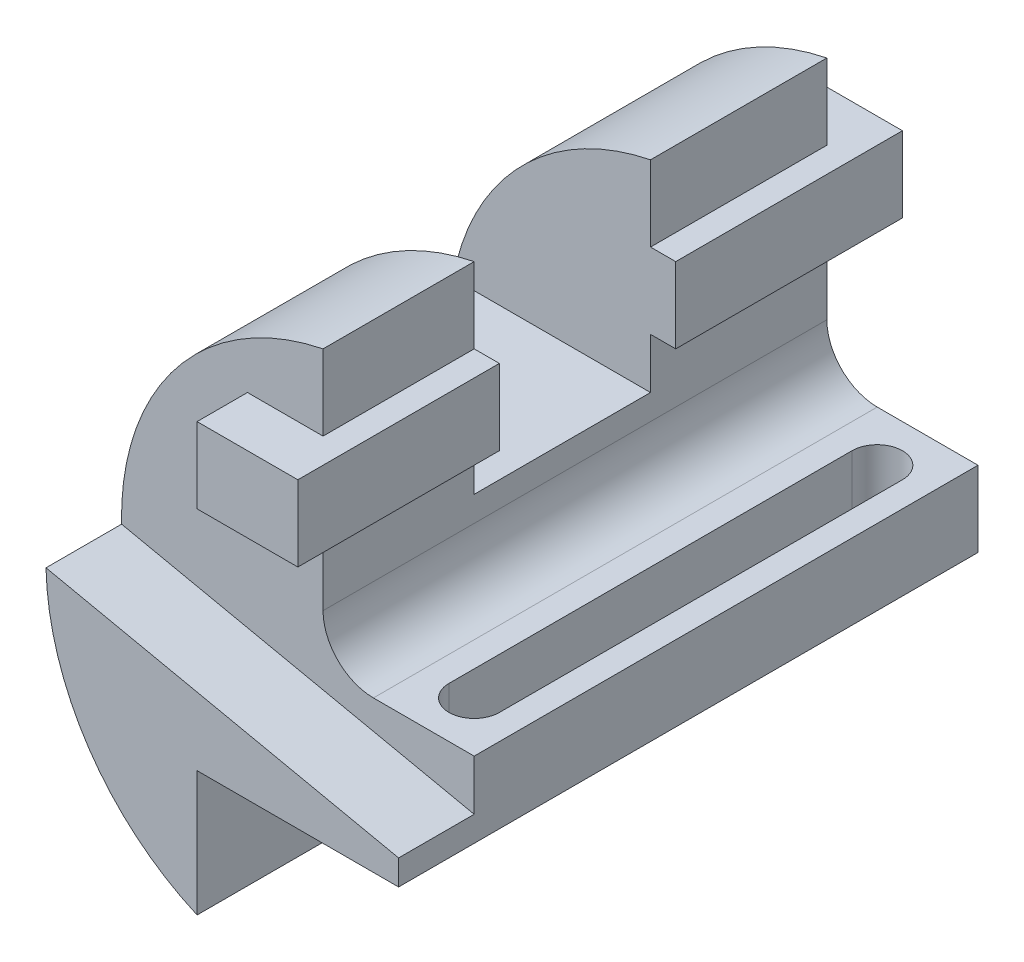
SolidWorks part; units mm, degrees
material "1060 Alloy"
ref_plane "Front Plane" through (0, 0, 0) normal (0, 0, 1) x (1, 0, 0)
ref_plane "Top Plane" through (0, 0, 0) normal (0, 1, 0) x (1, 0, 0)
ref_plane "Right Plane" through (0, 0, 0) normal (1, 0, 0) x (0, 0, -1)
sketch "Sketch1" plane through (0, 0, 0) normal (0, 0, 1) x (1, 0, 0)
  line L0 (0, 0) -> (0, 15)
  line L1 (0, 15) -> (-30, 15)
  line L2 (-30, 15) -> (-30, 70)
  line L3 (0, 0) -> (-40, 0)
  line L4 (-40, 0) -> (-40, -24.8156)
  arc A0 (-30, 70) -> (-40, -24.8156) centre (-20, 21.0102) ccw
  dimension "D5" = 50
  dimension "D1" = 15
  dimension "D2" = 20
  dimension "D3" = 40
  dimension "D4" = 10
  dimension "D6" = 55
extrude "Boss-Extrude2" add sketch "Sketch1" along normal blind 115
sketch "Sketch2" plane through (0, 0, 115) normal (0, 0, 1) x (1, 0, 0)
  line L0 (0, 5) -> (-69.9871, 19.8762)
  line L1 (0, 0) -> (0, 15) construction
  line L8 (-40, 0) -> (0, 0)
  line L9 (0, 0) -> (0, 15)
  line L10 (0, 15) -> (-30, 15)
  line L11 (-30, 15) -> (-30, 70)
  line L12 (-40, -24.8156) -> (-40, 0)
  line L14 (0, 5) -> (0, 15)
  line L15 (0, 15) -> (-30, 15)
  line L16 (-30, 15) -> (-30, 70)
  arc A0 (-30, 70) -> (-40, -24.8156) centre (-20, 21.0102) ccw construction
  arc A2 (-30, 70) -> (-40, -24.8156) centre (-20, 21.0102) ccw
  arc A3 (-30, 70) -> (-69.9871, 19.8762) centre (-20, 21.0102) ccw
  point P7 (0, 0)
  point P8 (0, 0)
  point P12 (0, 0)
  point P13 (0, 0)
  point P14 (0, 0)
  dimension "D1" = 5
  dimension "D2" = 78
  dimension "D3" = 0
extrude "Cut-Extrude1" cut sketch "Sketch2" against normal blind 15
sketch "Sketch4" plane through (0, 0, 0) normal (0, 0, -1) x (-1, 0, 0)
  line L0 (30, 15) -> (30, 70) construction
  line L1 (25, 55) -> (45, 55)
  line L2 (25, 55) -> (25, 40)
  line L3 (25, 40) -> (45, 40)
  line L4 (45, 55) -> (45, 40)
  dimension "D1" = 15
  dimension "D2" = 20
  dimension "D3" = 5
  dimension "D4" = 15
extrude "Boss-Extrude4" add sketch "Sketch4" against normal offset from surface 5 and the other way blind 10 up to face at (-31.3027, -0.8636, 115)
sketch "Sketch5" plane through (-30, 0, 0) normal (1, 0, 0) x (0, 0, -1)
  line L0 (-100, 70) -> (0, 70) construction
  line L1 (-70, 70) -> (-35, 70)
  line L2 (-70, 70) -> (-70, 30)
  line L3 (-70, 30) -> (-35, 30)
  line L4 (-35, 70) -> (-35, 30)
  line L5 (-100, 55) -> (-100, 70) construction
  line L6 (-100, 40) -> (0, 40) construction
  dimension "D1" = 30
  dimension "D2" = 35
  dimension "D3" = 10
extrude "Cut-Extrude3" cut sketch "Sketch5" against normal through all both and the other way through all
sketch "Sketch6" plane through (0, 15, 0) normal (0, 1, 0) x (1, 0, 0)
  line L0 (-10, -10) -> (-10, -90) construction
  line L1 (-5, -10) -> (-5, -90)
  line L2 (-15, -10) -> (-15, -90)
  line L3 (0, -100) -> (0, 0) construction
  line L4 (0, 0) -> (-30, 0) construction
  arc A0 (-5, -10) -> (-15, -10) centre (-10, -10) ccw
  arc A1 (-15, -90) -> (-5, -90) centre (-10, -90) ccw
  point P2 (-10, -50)
  dimension "D2" = 10
  dimension "D1" = 80
  dimension "D3" = 10
  dimension "D4" = 10
extrude "Cut-Extrude4" cut sketch "Sketch6" against normal through all both
fillet "Fillet1" radius 10 1 edges at (-30, 15, 50)
